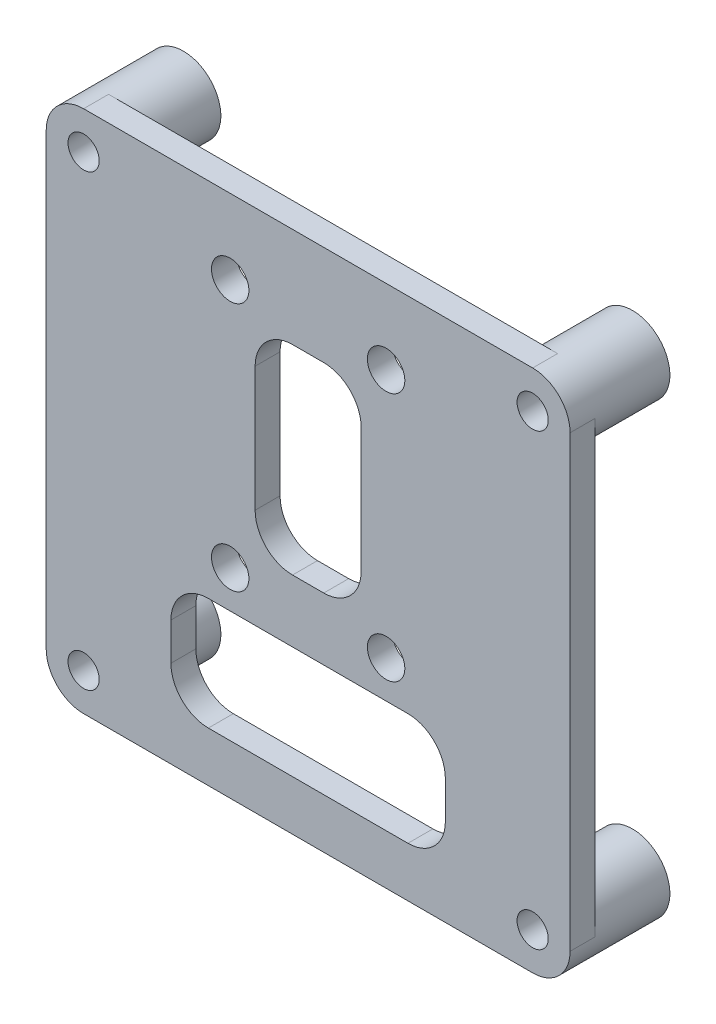
SolidWorks part; units mm, degrees
material "6061 合金"
ref_plane "前视基准面" through (0, 0, 0) normal (0, 0, 1) x (1, 0, 0)
ref_plane "上视基准面" through (0, 0, 0) normal (0, 1, 0) x (1, 0, 0)
ref_plane "右视基准面" through (0, 0, 0) normal (1, 0, 0) x (0, 0, -1)
other "Configuration Table"
sketch "草图1" plane through (0, 0, 0) normal (0, 0, 1) x (1, 0, 0)
  line L1 (-21, 21) -> (21, 21)
  line L2 (-21, 21) -> (-21, -21)
  line L3 (-21, -21) -> (21, -21)
  line L4 (21, 21) -> (21, -21)
  line L5 (-21, 21) -> (21, -21) construction
  line L6 (-21, -21) -> (21, 21) construction
  point P0 (0, 0)
  dimension "D1" = 42
  dimension "D2" = 42
extrude "凸台-拉伸1" add sketch "草图1" along normal blind 2
sketch "草图2" plane through (0, 0, 0) normal (0, 0, -1) x (-1, 0, 0)
  line L0 (-21, 21) -> (21, 21) construction
  line L1 (-21, -21) -> (-21, 21) construction
  line L2 (-6.25, 15) -> (6.25, 15) construction
  line L3 (-6.25, 15) -> (-6.25, -5) construction
  line L4 (6.25, 15) -> (6.25, -5) construction
  line L5 (-6.25, -5) -> (6.25, -5) construction
  line L6 (4.25, 13) -> (4.25, -3)
  line L7 (-4.25, -3) -> (4.25, -3)
  line L8 (-4.25, 13) -> (-4.25, -3)
  line L9 (-4.25, 13) -> (4.25, 13)
  line L10 (21, -21) -> (-21, -21) construction
  line L11 (-11, -8) -> (11, -8)
  line L12 (-11, -8) -> (-11, -17)
  line L13 (-11, -17) -> (11, -17)
  line L14 (11, -8) -> (11, -17)
  line L15 (-11, -8) -> (11, -17) construction
  line L16 (-11, -17) -> (11, -8) construction
  line L18 (-18, 18) -> (18, 18) construction
  line L19 (-18, 18) -> (-18, -18) construction
  line L20 (-18, -18) -> (18, -18) construction
  line L21 (18, 18) -> (18, -18) construction
  line L22 (-18, 18) -> (18, -18) construction
  line L23 (-18, -18) -> (18, 18) construction
  circle A0 centre (-6.25, 15) radius 1.5
  circle A1 centre (6.25, 15) radius 1.5
  circle A2 centre (6.25, -5) radius 1.5
  circle A3 centre (-6.25, -5) radius 1.5
  circle A4 centre (18, -18) radius 1.25
  circle A5 centre (-18, -18) radius 1.25
  circle A6 centre (-18, 18) radius 1.25
  circle A7 centre (18, 18) radius 1.25
  point P16 (0, -12.5)
  point P23 (0, 0)
  dimension "D4" = 14.75
  dimension "D5" = 3
  dimension "D14" = 2.5
  dimension "D3" = 6
  dimension "D6" = 2
  dimension "D7" = 3
  dimension "D8" = 4
  dimension "D9" = 20
  dimension "D10" = 36
  dimension "D11" = 36
  dimension "D15" = 7
  dimension "D16" = 7
  dimension "D1" = 2
  dimension "D2" = 2
  dimension "D12" = 2
  dimension "D13" = 2
extrude "切除-拉伸1" cut sketch "草图2" against normal blind 2
fillet "圆角1" radius 3 12 edges at (21, -21, 1) (-21, -21, 1) (-21, 21, 1) (21, 21, 1) (-4.25, -3, 1) (4.25, -3, 1) (-11, -17, 1) (11, -17, 1) (11, -8, 1) (-11, -8, 1) (4.25, 13, 1) (-4.25, 13, 1)
sketch "草图3" plane through (0, 0, 0) normal (0, 0, -1) x (-1, 0, 0)
  circle A0 centre (18, 18) radius 3
  circle A1 centre (18, -18) radius 3
  circle A2 centre (-18, -18) radius 3
  circle A3 centre (-18, 18) radius 3
  circle A4 centre (18, 18) radius 1.25
  circle A5 centre (18, -18) radius 1.25
  circle A6 centre (-18, -18) radius 1.2343
  circle A7 centre (-18, 18) radius 1.2395
  point P16 (0, 0)
extrude "凸台-拉伸2" add sketch "草图3" along normal blind 6
